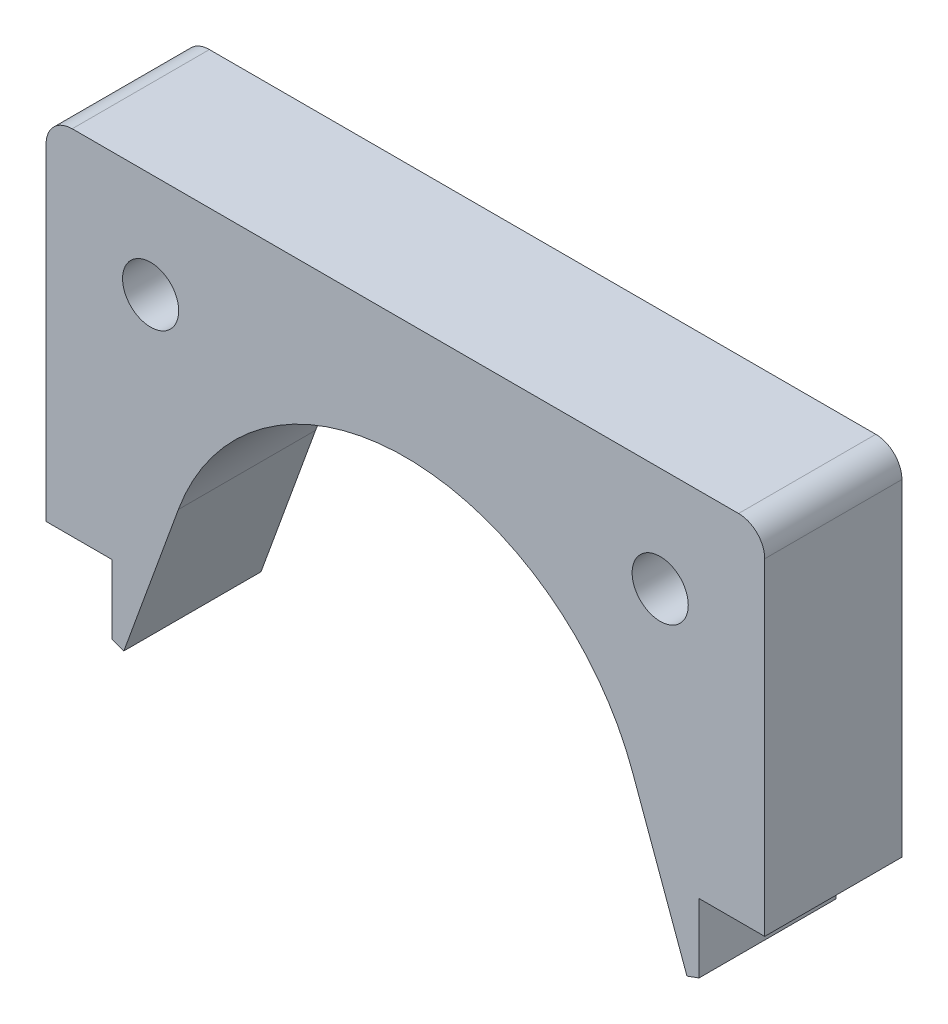
SolidWorks part; units mm, degrees
ref_plane "Front Plane" through (0, 0, 0) normal (0, 0, 1) x (1, 0, 0)
ref_plane "Top Plane" through (0, 0, 0) normal (0, 1, 0) x (1, 0, 0)
ref_plane "Right Plane" through (0, 0, 0) normal (1, 0, 0) x (0, 0, -1)
sketch "Sketch1" plane through (0, 0, 0) normal (0, 0, 1) x (1, 0, 0)
  line L1 (13.9441, -26.361) -> (14.8693, -26.6977)
  line L2 (14.8693, -26.6977) -> (19.0415, -15.2348)
  line L3 (53.7957, -15.2348) -> (57.9679, -26.6977)
  line L4 (63.9186, -49.0595) -> (63.9186, 5.9405) construction
  line L5 (63.9186, -21.0907) -> (63.9186, 5.9405)
  line L6 (63.9186, 5.9405) -> (8.9186, 5.9405)
  line L7 (8.9186, 5.9405) -> (8.9186, -21.0907)
  line L8 (57.9679, -26.6977) -> (58.8931, -26.361)
  line L9 (8.9186, -49.0595) -> (8.9186, 5.9405) construction
  line L10 (58.9931, -26.5907) -> (51.8369, -29.1953) construction
  line L11 (21.0003, -29.1953) -> (13.8441, -26.5907) construction
  line L12 (8.9186, -21.0907) -> (13.9441, -21.0907)
  line L13 (13.9441, -21.0907) -> (13.9441, -26.361)
  line L15 (63.9186, -21.0907) -> (58.8931, -21.0907)
  line L16 (19.0415, -15.2348) -> (6.5593, -49.5295) construction
  line L17 (21.3617, -29.3268) -> (13.8441, -26.5907) construction
  line L18 (58.8931, -21.0907) -> (58.8931, -26.361)
  line L19 (13.8441, -26.5907) -> (13.8441, -21.5907) construction
  line L20 (13.8441, -21.5907) -> (8.9186, -21.5907) construction
  arc A0 (19.0415, -15.2348) -> (53.7957, -15.2348) centre (36.4186, -21.5595) cw
  circle A1 centre (36.4186, -21.5595) radius 18.4923 construction
  circle A2 centre (55.9186, -2.0595) radius 2.15
  circle A3 centre (16.9186, -2.0595) radius 2.15
  circle A4 centre (16.9186, -2.0595) radius 2.15 construction
  circle A5 centre (55.9186, -2.0595) radius 2.15 construction
  dimension "D1" = 0.1
  dimension "D2" = 0.25
  dimension "D3" = 0.5
extrude "Boss-Extrude1" add sketch "Sketch1" along normal up to vertex (10.5 mm away)
fillet "Fillet1" radius 2 2 edges at (63.9186, 5.9405, 5.25) (8.9186, 5.9405, 5.25)
